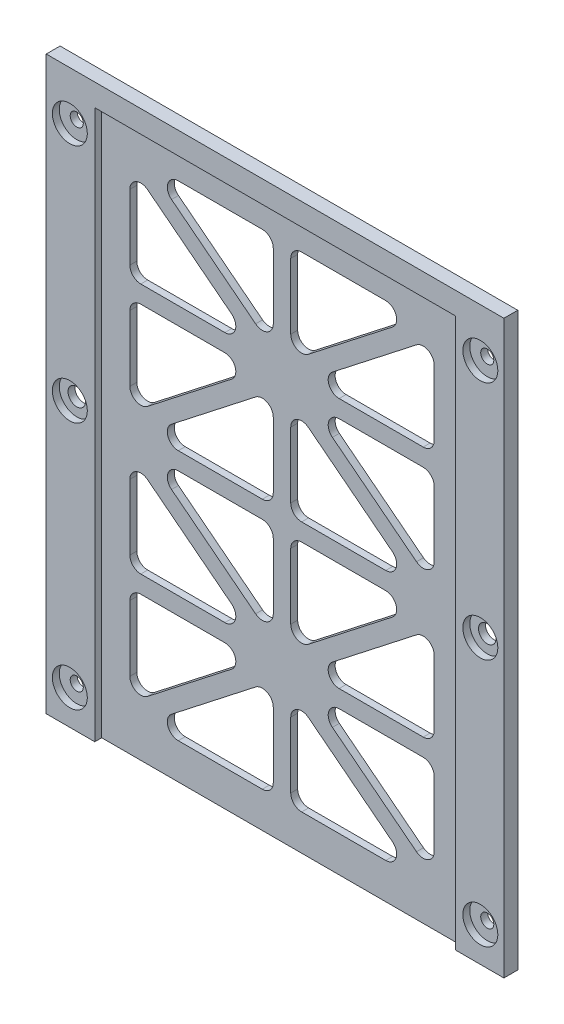
SolidWorks part; units mm, degrees
material "1060 Alloy"
ref_plane "Front Plane" through (0, 0, 0) normal (0, 0, 1) x (1, 0, 0)
ref_plane "Top Plane" through (0, 0, 0) normal (0, 1, 0) x (1, 0, 0)
ref_plane "Right Plane" through (0, 0, 0) normal (1, 0, 0) x (0, 0, -1)
sketch "Sketch1" plane through (0, 0, 0) normal (0, 0, 1) x (1, 0, 0)
  line L0 (0, -121.5331) -> (0, -64.0331) construction
  line L1 (4, 104.4669) -> (4, 59.1638)
  line L2 (62.0353, 104.4669) -> (4, 59.1638)
  line L3 (0, -121.5331) -> (73.66, -121.5331) construction
  line L4 (73.66, -121.5331) -> (73.66, -64.0331) construction
  line L5 (0, 117.5409) -> (0, -133.9191)
  line L6 (0, -133.9191) -> (104.775, -133.9191)
  line L7 (0, -64.0331) -> (73.66, -121.5331) construction
  line L8 (0, -64.0331) -> (73.66, -64.0331) construction
  line L9 (73.66, -64.0331) -> (73.66, -6.5331) construction
  line L10 (73.66, -6.5331) -> (0, -64.0331) construction
  line L11 (0, -64.0331) -> (0, -6.5331) construction
  line L12 (0, -6.5331) -> (73.66, -6.5331) construction
  line L13 (73.66, -6.5331) -> (0, 50.9669) construction
  line L14 (0, 50.9669) -> (0, -6.5331) construction
  line L15 (0, 50.9669) -> (73.66, 50.9669) construction
  line L16 (73.66, 50.9669) -> (73.66, -6.5331) construction
  line L17 (73.66, 50.9669) -> (73.66, 108.4669) construction
  line L18 (73.66, 108.4669) -> (0, 50.9669) construction
  line L19 (0, 108.4669) -> (73.66, 108.4669) construction
  line L20 (0, 108.4669) -> (0, 50.9669) construction
  line L21 (4, 104.4669) -> (62.0353, 104.4669)
  line L22 (69.66, 100.2701) -> (11.6247, 54.9669)
  line L23 (11.6247, 54.9669) -> (69.66, 54.9669)
  line L24 (69.66, 54.9669) -> (69.66, 100.2701)
  line L25 (11.6247, 46.9669) -> (69.66, 46.9669)
  line L26 (69.66, 46.9669) -> (69.66, 1.6638)
  line L27 (69.66, 1.6638) -> (11.6247, 46.9669)
  line L28 (62.0353, -2.5331) -> (4, 42.7701)
  line L29 (4, 42.7701) -> (4, -2.5331)
  line L30 (4, -2.5331) -> (62.0353, -2.5331)
  line L31 (4, -10.5331) -> (62.0353, -10.5331)
  line L32 (62.0353, -10.5331) -> (4, -55.8362)
  line L33 (4, -55.8362) -> (4, -10.5331)
  line L34 (69.66, -14.7299) -> (11.6247, -60.0331)
  line L35 (11.6247, -60.0331) -> (69.66, -60.0331)
  line L36 (69.66, -60.0331) -> (69.66, -14.7299)
  line L37 (11.6247, -68.0331) -> (69.66, -68.0331)
  line L38 (69.66, -113.3362) -> (69.66, -68.0331)
  line L39 (11.6247, -68.0331) -> (69.66, -113.3362)
  line L40 (4, -117.5331) -> (4, -72.2299)
  line L41 (4, -72.2299) -> (62.0353, -117.5331)
  line L42 (4, -117.5331) -> (62.0353, -117.5331)
  line L43 (104.775, -133.9191) -> (104.775, 117.5409)
  line L44 (104.775, 117.5409) -> (0, 117.5409)
  point P0 (0, 0)
  dimension "D12" = 251.46
  dimension "D2" = 230
  dimension "D11" = 73.66
  dimension "D13" = 104.775
  dimension "D3" = 4
  dimension "D4" = 4
  dimension "D5" = 4
  dimension "D6" = 4
  dimension "D7" = 4
  dimension "D8" = 4
  dimension "D9" = 4
  dimension "D10" = 4
extrude "Boss-Extrude2" add sketch "Sketch1" along normal blind 3.175
ref_plane "Plane1" through (0, 0, 6.35) normal (0, 0, -1) x (-1, 0, 0)
fillet "Cutout_Fillets" radius 5 24 edges at (4, 59.1638, 1.5875) (62.0353, 104.4669, 1.5875) (4, 104.4669, 1.5875) (11.6247, 54.9669, 1.5875) (69.66, 54.9669, 1.5875) (69.66, 100.2701, 1.5875) (69.66, 1.6638, 1.5875) (69.66, 46.9669, 1.5875) (11.6247, 46.9669, 1.5875) (4, -2.5331, 1.5875) (4, 42.7701, 1.5875) (62.0353, -2.5331, 1.5875) (62.0353, -10.5331, 1.5875) (4, -10.5331, 1.5875) (4, -55.8362, 1.5875) (69.66, -60.0331, 1.5875) (69.66, -14.7299, 1.5875) (11.6247, -60.0331, 1.5875) (11.6247, -68.0331, 1.5875) (69.66, -68.0331, 1.5875) (69.66, -113.3362, 1.5875) (62.0353, -117.5331, 1.5875) (4, -117.5331, 1.5875) (4, -72.2299, 1.5875)
sketch "Sketch2" plane through (0, 0, 3.175) normal (0, 0, 1) x (1, 0, 0)
  line L0 (104.775, 117.5409) -> (0, 117.5409) construction
  line L1 (82.55, 117.5409) -> (104.775, 117.5409)
  line L2 (82.55, 117.5409) -> (82.55, -133.9191)
  line L3 (82.55, -133.9191) -> (104.775, -133.9191)
  line L4 (104.775, 117.5409) -> (104.775, -133.9191)
  line L5 (0, -133.9191) -> (104.775, -133.9191) construction
  line L6 (104.775, -133.9191) -> (104.775, 117.5409) construction
  line L9 (0, 117.5409) -> (0, -133.9191) construction
  circle A0 centre (93.98, -118.1153) radius 8
  circle A1 centre (93.98, -4.3791) radius 8
  circle A2 centre (93.98, 105.5409) radius 8
  dimension "D1" = 16
  dimension "D2" = 82.55
  dimension "D3" = 11.43
  dimension "D4" = 12
  dimension "D5" = 129.54
extrude "Boss-Extrude3" add sketch "Sketch2" along normal up to surface (3.175 mm away) up to plane "Plane1"
sketch "Sketch3" plane through (0, 0, 6.35) normal (0, 0, 1) x (1, 0, 0)
  circle A0 centre (93.98, 105.5409) radius 3
  circle A1 centre (93.98, -4.3791) radius 4
  circle A2 centre (93.98, -118.1153) radius 3
  dimension "D1" = 8
  dimension "D2" = 6
extrude "Cut-Extrude1" cut sketch "Sketch3" against normal blind 30
mirror "Mirror2" of "Cut-Extrude1", "Boss-Extrude2", "Cutout_Fillets", "Boss-Extrude3"
sketch "Sketch4" plane through (0, 117.5409, 0) normal (0, 1, 0) x (1, 0, 0)
  line L0 (104.775, -6.35) -> (104.775, 0) construction
  line L1 (-104.775, 0) -> (104.775, 0)
  line L2 (-104.775, 0) -> (-104.775, -6.35)
  line L3 (-104.775, -6.35) -> (104.775, -6.35)
  line L4 (104.775, 0) -> (104.775, -6.35)
  dimension "D1" = 6.35
extrude "Boss-Extrude4" add sketch "Sketch4" along normal blind 10.16
sketch "Sketch5" plane through (0, 117.5409, 0) normal (0, -1, 0) x (1, 0, 0)
  circle A0 centre (0, 15.2337) radius 3
  circle A1 centre (17, 15.2337) radius 3
  circle A2 centre (34, 15.2337) radius 3
  circle A3 centre (51, 15.2337) radius 3
  circle A4 centre (68, 15.2337) radius 3
  circle A5 centre (-17, 15.2337) radius 3
  circle A6 centre (-34, 15.2337) radius 3
  circle A7 centre (-51, 15.2337) radius 3
  circle A8 centre (-68, 15.2337) radius 3
  dimension "D1" = 6
  dimension "D2" = 5
  dimension "D3" = 5
extrude "Cut-Extrude2" [suppressed] cut sketch "Sketch5" against normal blind 10
